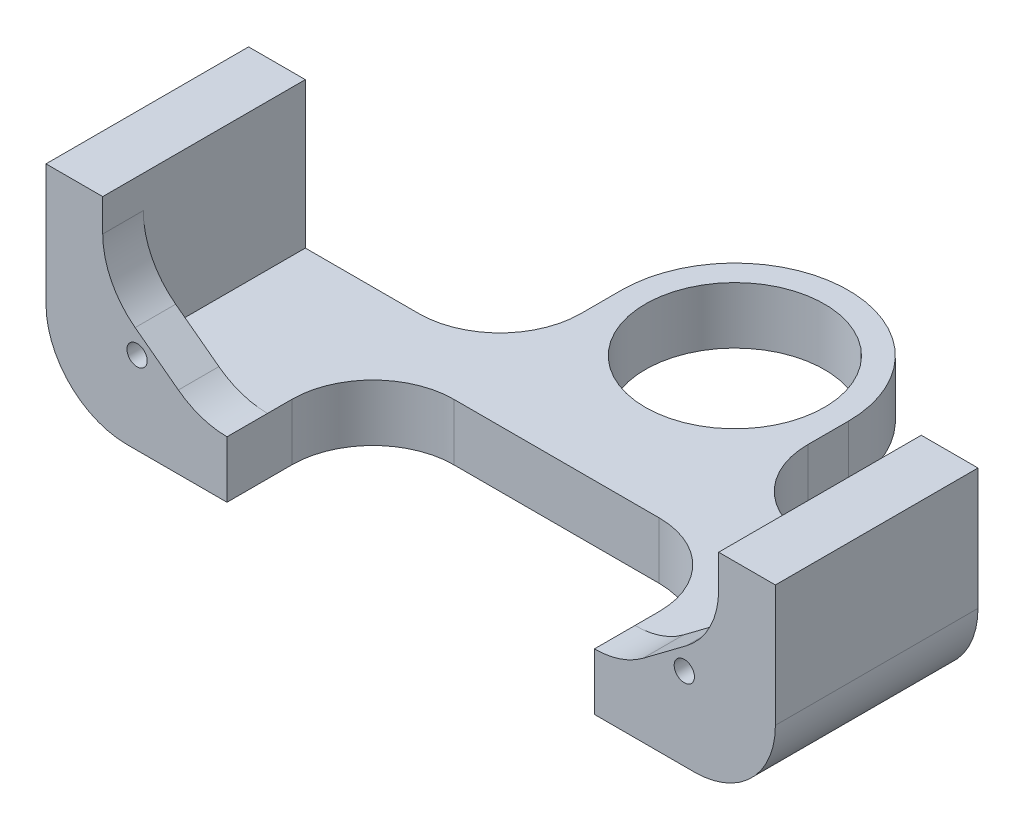
SolidWorks part; units mm, degrees
material "PVC 0.007 Plasticized"
ref_plane "Front Plane" through (0, 0, 0) normal (0, 0, 1) x (1, 0, 0)
ref_plane "Top Plane" through (0, 0, 0) normal (0, 1, 0) x (1, 0, 0)
ref_plane "Right Plane" through (0, 0, 0) normal (1, 0, 0) x (0, 0, -1)
sketch "Sketch1" plane through (0, 0, 0) normal (0, 1, 0) x (1, 0, 0)
  line L2 (0, 0) -> (0, -40)
  line L3 (0, -40) -> (28, -40)
  line L4 (28, 0) -> (28, -40)
  arc A0 (28, 0) -> (0, 0) centre (14, 0) ccw
  circle A1 centre (14, 0) radius 11.05
  dimension "D3" = 22.1
  dimension "D1" = 40
  dimension "D2" = 28
extrude "Boss-Extrude1" add sketch "Sketch1" along normal blind 7
sketch "Sketch2" plane through (0, 0, 40) normal (0, 0, 1) x (1, 0, 0)
  line L0 (28, 0) -> (59, 0)
  line L1 (59, 0) -> (59, 25)
  line L2 (59, 25) -> (52, 25)
  line L3 (52, 25) -> (52, 7) construction
  line L4 (52, 7) -> (28, 7) construction
  line L5 (28, 7) -> (28, 0) construction
  line L6 (0, 0) -> (28, 0) construction
  line L7 (52, 16) -> (40, 7)
  line L8 (40, 7) -> (28, 7)
  line L9 (52, 16) -> (52, 25)
  line L10 (46, 11.5) -> (52, 7) construction
  circle A0 centre (47.76, 10.18) radius 1.25
  point P13 (14, 0)
  line M8 (28, 0) -> (28, 7)
  dimension "D3" = 2.5
  dimension "D1" = 45
  dimension "D2" = 25
  dimension "D4" = 2.2
extrude "Boss-Extrude2" add sketch "Sketch2" against normal blind 5 contours L9 L7 L8 L0 L1 L2 A0 M8
sketch "Sketch3" plane through (0, 0, 35) normal (0, 0, -1) x (-1, 0, 0)
  line L0 (-52, 16) -> (-52, 7)
  line L1 (-52, 7) -> (-40, 7)
  line L7 (-52, 16) -> (-52, 25)
  line L8 (-52, 25) -> (-59, 25)
  line L9 (-59, 25) -> (-59, 0)
  line L10 (-59, 0) -> (-28, 0)
  line L11 (-28, 0) -> (-28, 7)
  line L12 (-28, 7) -> (-40, 7)
  line L13 (-40, 7) -> (-52, 16)
  line L14 (-52, 16) -> (-52, 25)
  line L15 (-52, 25) -> (-59, 25)
  line L16 (-59, 25) -> (-59, 0)
  line L17 (-59, 0) -> (-28, 0)
  line L18 (-28, 0) -> (-28, 7)
  line L19 (-28, 7) -> (-40, 7)
  dimension "D1" = 0
extrude "Boss-Extrude3" add sketch "Sketch3" along normal blind 20
ref_plane "Plane1" through (14, 0, 0) normal (1, 0, 0) x (0, 0, -1)
mirror "Mirror1" about plane through (14, 0, 0) normal (1, 0, 0) of "Boss-Extrude3", "Boss-Extrude2"
fillet "Fillet1" radius 10 8 edges at (52, 16, 37.5) (59, 0, 27.5) (40, 7, 37.5) (28, 3.5, 15) (-24, 16, 37.5) (-12, 7, 37.5) (-31, 0, 27.5) (0, 3.5, 15)
sketch "Sketch5" plane through (0, 7, 0) normal (0, 1, 0) x (1, 0, 0)
  line L0 (-8.6667, -35) -> (-8.6667, -40) construction
  line L1 (-8.6667, -22) -> (36.6667, -22)
  line L2 (-8.6667, -22) -> (-8.6667, -40)
  line L3 (-8.6667, -40) -> (36.6667, -40)
  line L4 (36.6667, -22) -> (36.6667, -40)
  dimension "D1" = 18
extrude "Cut-Extrude2" cut sketch "Sketch5" against normal up to surface (7 mm away) up to face at (14, 0, 14.0142)
fillet "Fillet2" radius 10 2 edges at (36.6667, 3.5, 22) (-8.6667, 3.5, 22)
